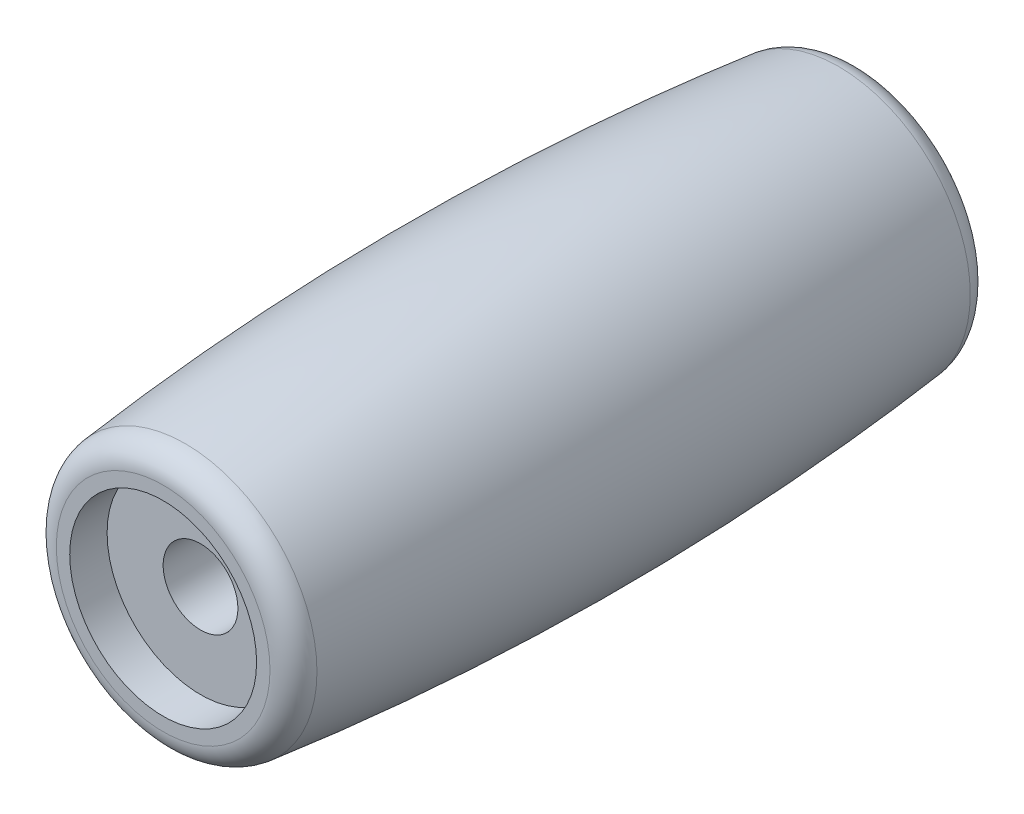
SolidWorks part; units mm, degrees
ref_plane "前视基准面" through (0, 0, 0) normal (0, 0, 1) x (1, 0, 0)
ref_plane "上视基准面" through (0, 0, 0) normal (0, 1, 0) x (1, 0, 0)
ref_plane "右视基准面" through (0, 0, 0) normal (1, 0, 0) x (0, 0, -1)
sketch "草图2" plane through (0, 0, 0) normal (1, 0, 0) x (0, 0, -1)
  line L0 (3.8519, 0) -> (3.8519, 6) construction
  line L1 (3.8519, 0) -> (15.453, 0) construction
  line L2 (-8.6481, 1.5) -> (16.3519, 1.5)
  line L3 (16.3519, 1.5) -> (16.3519, 3.75)
  line L4 (16.3519, 3.75) -> (17.8519, 3.75)
  line L5 (17.8519, 3.75) -> (17.8519, 4.2878)
  line L6 (3.8519, 6) -> (-3.6217, 6) construction
  line L7 (-10.1481, 3.75) -> (-10.1481, 4.2878)
  line L8 (-8.6481, 3.75) -> (-10.1481, 3.75)
  line L9 (-8.6481, 1.5) -> (-8.6481, 3.75)
  arc A0 (17.8519, 4.2878) -> (16.9612, 5.2818) centre (16.8519, 4.2878) ccw
  arc A1 (16.9612, 5.2818) -> (-9.2573, 5.2818) centre (3.8519, -114) ccw
  arc A2 (-10.1481, 4.2878) -> (-9.2573, 5.2818) centre (-9.1481, 4.2878) cw
  point P19 (3.8519, 1.5)
  dimension "D1" = 1
  dimension "D7" = 120
  dimension "D2" = 3
  dimension "D3" = 14
  dimension "D4" = 1.5
  dimension "D5" = 7.5
  dimension "D6" = 12
revolve "旋转1" add sketch "草图2" angle 360 about L1
